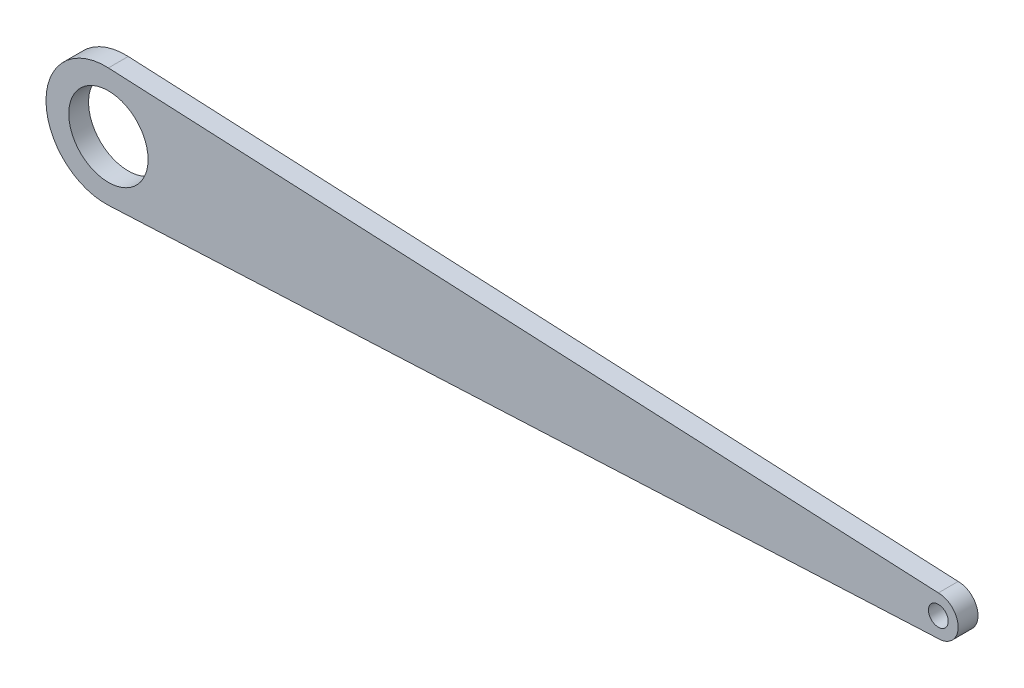
SolidWorks part; units mm, degrees
ref_plane "Plano frontal" through (0, 0, 0) normal (0, 0, 1) x (1, 0, 0)
ref_plane "Plano superior" through (0, 0, 0) normal (0, 1, 0) x (1, 0, 0)
ref_plane "Plano direito" through (0, 0, 0) normal (1, 0, 0) x (0, 0, -1)
sketch "Esboço1" plane through (0, 0, 0) normal (0, 0, 1) x (1, 0, 0)
  line L1 (-104.635, 0) -> (104.635, 0) construction
  line L5 (-104.635, -15) -> (104.635, -5)
  line L7 (-104.635, 15) -> (104.635, 5)
  arc A1 (104.635, 5) -> (104.635, -5) centre (104.635, 0) cw
  circle A2 centre (-104.635, 0) radius 10
  circle A3 centre (104.635, 0) radius 2.5
  arc A7 (-104.635, 15) -> (-104.635, -15) centre (-105.3518, 0) ccw
  point P3 (0, 5)
  dimension "D1" = 209.27
extrude "Ressalto-extrusão1" add sketch "Esboço1" along normal blind 5
